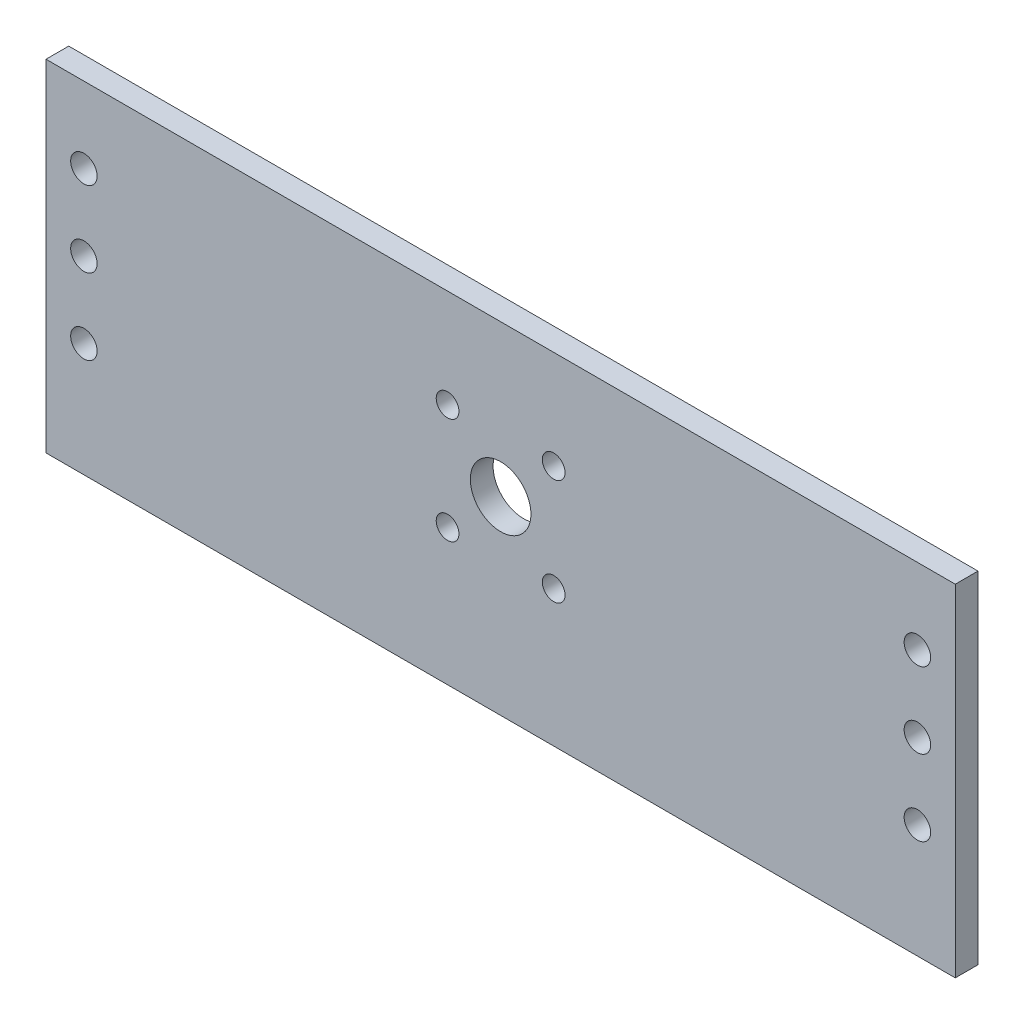
SolidWorks part; units mm, degrees
ref_plane "Plan de face" through (0, 0, 0) normal (0, 0, 1) x (1, 0, 0)
ref_plane "Plan de dessus" through (0, 0, 0) normal (0, 1, 0) x (1, 0, 0)
ref_plane "Plan de droite" through (0, 0, 0) normal (1, 0, 0) x (0, 0, -1)
sketch "Esquisse1" plane through (0, 0, 0) normal (0, 0, 1) x (1, 0, 0)
  line L1 (60, -22.5) -> (-60, -22.5)
  line L2 (60, -22.5) -> (60, 22.5)
  line L3 (60, 22.5) -> (-60, 22.5)
  line L4 (-60, -22.5) -> (-60, 22.5)
  line L5 (60, -22.5) -> (-60, 22.5) construction
  line L6 (60, 22.5) -> (-60, -22.5) construction
  point P0 (0, 0)
  dimension "D1" = 45
  dimension "D2" = 120
extrude "Boss.-Extru.1" add sketch "Esquisse1" along normal blind 3
sketch "Esquisse2" plane through (0, 0, 3) normal (0, 0, 1) x (1, 0, 0)
  line L0 (60, 22.5) -> (-60, 22.5) construction
  line L2 (-55, 12.5) -> (60, 12.5) construction
  line L3 (60, -22.5) -> (60, 22.5) construction
  line L4 (-55, 12.5) -> (-55, -22.5) construction
  line L5 (-60, -22.5) -> (60, -22.5) construction
  line L6 (-7, 9.5) -> (7, 9.5) construction
  line L7 (0, 0) -> (0, -22.5) construction
  line L8 (7, -9.5) -> (-7, -9.5) construction
  line L9 (12, -4.5) -> (12, 9.5) construction
  line L10 (7, 14.5) -> (-7, 14.5) construction
  line L11 (-12, -4.5) -> (-12, 9.5) construction
  line L12 (12, -9.5) -> (-12, 14.5) construction
  line L13 (12, 14.5) -> (-12, -9.5) construction
  line L14 (-7, 9.5) -> (-7, -4.5) construction
  line L15 (55, 12.5) -> (55, -22.5) construction
  circle A0 centre (-55, 12.5) radius 1.7476
  circle A2 centre (55, 12.5) radius 1.7476
  circle A3 centre (-55, 2.5) radius 1.7476
  circle A4 centre (-55, -7.5) radius 1.7476
  circle A12 centre (55, -7.5) radius 1.7476
  circle A13 centre (55, 2.5) radius 1.7476
  circle A15 centre (0, 2.5) radius 4
  arc A16 (7, -9.5) -> (12, -4.5) centre (7, -4.5) ccw construction
  arc A17 (-7, -9.5) -> (-12, -4.5) centre (-7, -4.5) cw construction
  arc A18 (12, 9.5) -> (7, 14.5) centre (7, 9.5) ccw construction
  arc A19 (-7, 14.5) -> (-12, 9.5) centre (-7, 9.5) ccw construction
  circle A20 centre (-7, 9.5) radius 1.5
  circle A21 centre (7, 9.5) radius 1.5
  circle A22 centre (7, -4.5) radius 1.5
  circle A23 centre (-7, -4.5) radius 1.5
  circle A25 centre (0, 12.5) radius 1.7476 [skipped]
  dimension "D7" = 14
  dimension "D8" = 8
  dimension "D10" = 5
  dimension "D12" = 3
  dimension "D1" = 10
  dimension "D2" = 15
  dimension "D4" = 5
  dimension "D6" = 14
  dimension "D9" = 10
  dimension "30" = 25
  dimension "D11" = 14
  dimension "D3" = 3
  dimension "D5" = 3
  dimension "D13" = 2
  dimension "D14" = 2
extrude "Enlèv. mat.-Extru.1" cut sketch "Esquisse2" against normal blind 10
